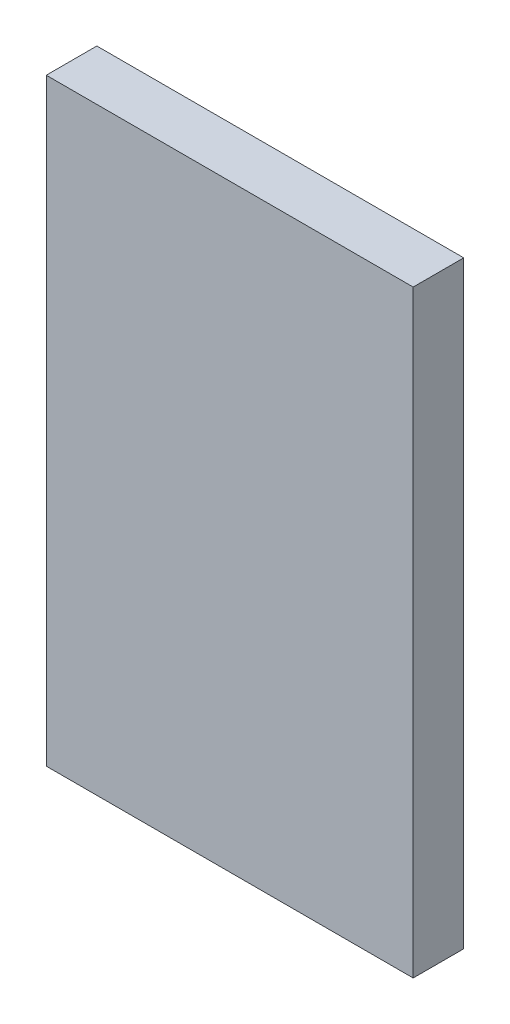
SolidWorks part; units mm, degrees
ref_plane "Alzado" through (0, 0, 0) normal (0, 0, 1) x (1, 0, 0)
ref_plane "Planta" through (0, 0, 0) normal (0, 1, 0) x (1, 0, 0)
ref_plane "Vista lateral" through (0, 0, 0) normal (1, 0, 0) x (0, 0, -1)
sketch "Croquis1" plane through (0, 0, 0) normal (0, 0, 1) x (1, 0, 0)
  line L1 (-609.3061, 400.5015) -> (137.9163, 400.5015)
  line L2 (-609.3061, 400.5015) -> (-609.3061, -818.1181)
  line L3 (-609.3061, -818.1181) -> (137.9163, -818.1181)
  line L4 (137.9163, 400.5015) -> (137.9163, -818.1181)
extrude "Saliente-Extruir1" add sketch "Croquis1" along normal blind 103
